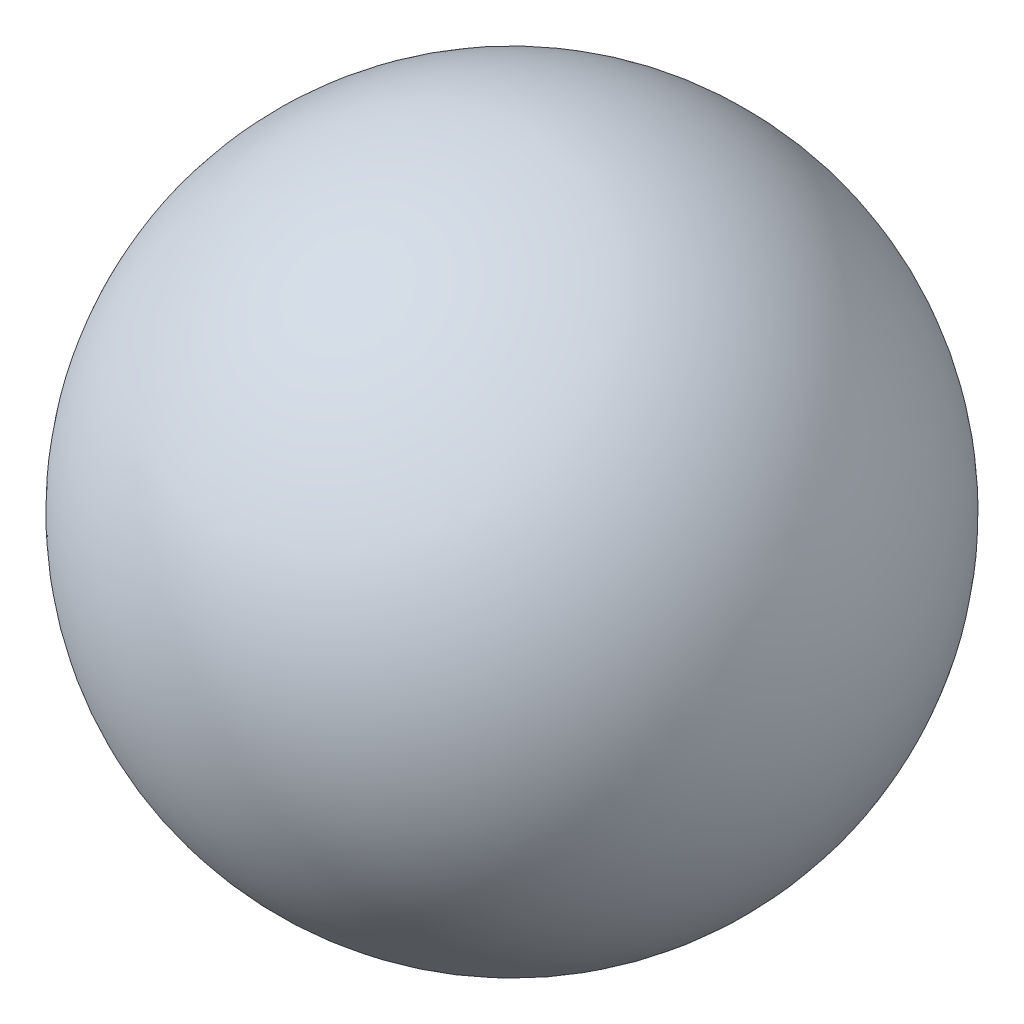
SolidWorks part; units mm, degrees
ref_plane "Front Plane" through (0, 0, 0) normal (0, 0, 1) x (1, 0, 0)
ref_plane "Top Plane" through (0, 0, 0) normal (0, 1, 0) x (1, 0, 0)
ref_plane "Right Plane" through (0, 0, 0) normal (1, 0, 0) x (0, 0, -1)
sketch "Sketch1" plane through (0, 0, 0) normal (0, 0, 1) x (1, 0, 0)
  line L0 (-12, 0) -> (12, 0)
  arc A0 (12, 0) -> (-12, 0) centre (0, 0) cw
  dimension "D1" = 24
revolve "Revolve1" add sketch "Sketch1" angle 360 about L0
scale "Scale1" scale about centroid uniform scaling yes scale factor 0.2
scale "Scale2" scale about centroid uniform scaling yes scale factor 1.9329
scale "Scale3" scale about centroid uniform scaling yes scale factor 1.5
